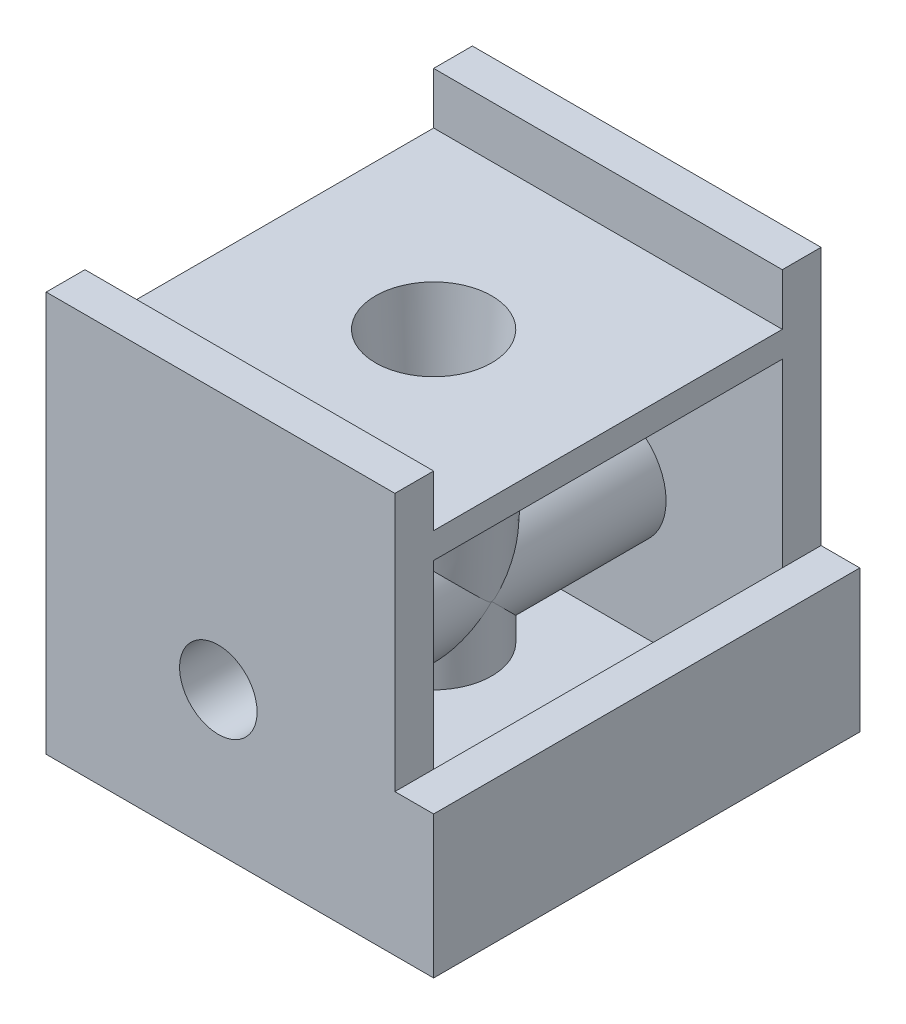
SolidWorks part; units mm, degrees
ref_plane "Front Plane" through (0, 0, 0) normal (0, 0, 1) x (1, 0, 0)
ref_plane "Top Plane" through (0, 0, 0) normal (0, 1, 0) x (1, 0, 0)
ref_plane "Right Plane" through (0, 0, 0) normal (1, 0, 0) x (0, 0, -1)
sketch "Sketch1" plane through (0, 0, 0) normal (0, 1, 0) x (1, 0, 0)
  line L0 (-16.5, 16.5) -> (16.5, 16.5)
  line L1 (-13.5, 13.5) -> (13.5, 13.5)
  line L2 (-13.5, 13.5) -> (-13.5, -13.5)
  line L3 (-13.5, -13.5) -> (13.5, -13.5)
  line L4 (13.5, 13.5) -> (13.5, -13.5)
  line L5 (-13.5, 13.5) -> (13.5, -13.5) construction
  line L6 (-13.5, -13.5) -> (13.5, 13.5) construction
  line L7 (16.5, 16.5) -> (16.5, -16.5)
  line L8 (-16.5, -16.5) -> (16.5, -16.5)
  line L9 (-16.5, 16.5) -> (-16.5, -16.5)
  point P0 (0, 0)
  dimension "D1" = 27
  dimension "D2" = 27
  dimension "D3" = 3
extrude "Boss-Extrude1" add sketch "Sketch1" along normal blind 30
sketch "Sketch3" plane through (-13.5, 0, 0) normal (1, 0, 0) x (0, 0, -1)
  line L1 (-13.5, 0) -> (13.5, 0)
  line L2 (-13.5, 0) -> (-13.5, 30)
  line L3 (-13.5, 30) -> (13.5, 30)
  line L4 (13.5, 0) -> (13.5, 30)
extrude "Cut-Extrude1" cut sketch "Sketch3" against normal blind 30
sketch "Sketch4" plane through (16.5, 0, 0) normal (1, 0, 0) x (0, 0, -1)
  line L1 (-16.5, 0) -> (16.5, 0)
  line L2 (-16.5, 0) -> (-16.5, -1)
  line L3 (-16.5, -1) -> (16.5, -1)
  line L4 (16.5, 0) -> (16.5, -1)
extrude "Boss-Extrude2" add sketch "Sketch4" against normal up to vertex (33 mm away)
sketch "Sketch5" plane through (13.5, 0, 0) normal (-1, 0, 0) x (0, 0, 1)
  line L0 (-13.5, 0) -> (-13.5, 24.4707)
  line L1 (-13.5, 30) -> (-13.5, 0) construction
  line L2 (13.5, 30) -> (13.5, 0) construction
  line L3 (-13.5, 24.4707) -> (13.5, 24.4707)
  line L4 (-13.5, 24.4707) -> (-13.5, 22.4707)
  line L5 (-13.5, 22.4707) -> (13.5, 22.4707)
  line L6 (13.5, 24.4707) -> (13.5, 22.4707)
sketch "Sketch7" plane through (0, 0, 0) normal (0, 1, 0) x (1, 0, 0)
  line L0 (13.5, 13.5) -> (9.5, 13.5)
  line L1 (13.5, 13.5) -> (-16.5, 13.5) construction
  line L2 (9.5, 13.5) -> (13.5, 9.5)
  line L3 (13.5, -13.5) -> (13.5, 13.5) construction
  line L4 (13.5, 9.5) -> (13.5, 13.5)
extrude "Boss-Extrude4" add sketch "Sketch7" along normal blind 4.8
sketch "Sketch8" plane through (0, 0, 0) normal (0, 1, 0) x (1, 0, 0)
  line L0 (13.5, 9.5) -> (9.5, 13.5)
  line L1 (9.5, 13.5) -> (13.5, 13.5)
  line L2 (13.5, 13.5) -> (13.5, 9.5)
extrude "Cut-Extrude3" cut sketch "Sketch8" along normal blind 2.8
sketch "Sketch9" plane through (0, 0, 0) normal (0, 1, 0) x (1, 0, 0)
  line L0 (13.5, -13.5) -> (13.5, -9.5)
  line L1 (13.5, -13.5) -> (13.5, 13.5) construction
  line L2 (13.5, -9.5) -> (9.5, -13.5)
  line L3 (-16.5, -13.5) -> (13.5, -13.5) construction
  line L4 (9.5, -13.5) -> (13.5, -13.5)
extrude "Boss-Extrude5" add sketch "Sketch9" along normal blind 4.8
sketch "Sketch10" plane through (0, 0, 0) normal (0, 1, 0) x (1, 0, 0)
  line L0 (9.5, -13.5) -> (13.5, -9.5)
  line L1 (13.5, -9.5) -> (13.5, -13.5)
  line L2 (13.5, -13.5) -> (9.5, -13.5)
extrude "Cut-Extrude5" cut sketch "Sketch10" along normal blind 2.8
sketch "Sketch12" plane through (0, 0, 0) normal (0, 1, 0) x (1, 0, 0)
  line L1 (13.5, 13.5) -> (-16.5, 13.5)
  line L2 (13.5, 13.5) -> (13.5, -13.5)
  line L3 (13.5, -13.5) -> (-16.5, -13.5)
  line L4 (-16.5, 13.5) -> (-16.5, -13.5)
  line L5 (-16.5, -13.5) -> (-13.5, -13.5)
  line L6 (-16.5, -13.5) -> (-16.5, 13.5)
  line L7 (-16.5, 13.5) -> (-13.5, 13.5)
  line L8 (-13.5, -13.5) -> (-13.5, 13.5)
  line M2 (-16.5, -13.5) -> (13.5, -13.5)
  line M5 (-16.5, 13.5) -> (-16.5, -13.5)
extrude "Cut-Extrude6" cut sketch "Sketch12" against normal blind 10 contours L8 L1 M2 M5
sketch "Sketch13" plane through (0, -1, 0) normal (0, -1, 0) x (1, 0, 0)
  line L1 (-16.5, 16.5) -> (-13.5, 16.5)
  line L2 (-16.5, 16.5) -> (-16.5, -20.8947)
  line L3 (-16.5, -20.8947) -> (-13.5, -20.8947)
  line L4 (-13.5, 16.5) -> (-13.5, -20.8947)
extrude "Cut-Extrude7" cut sketch "Sketch13" against normal through all
sketch "Sketch15" plane through (0, 0, 16.5) normal (0, 0, 1) x (1, 0, 0)
  line L0 (16.5, 30) -> (16.5, -1) construction
  line L1 (-13.5, -1) -> (16.5, -1)
  line L2 (-13.5, -1) -> (-13.5, 0)
  line L3 (-13.5, 0) -> (13.5, 0) construction
  line L4 (16.5, -1) -> (16.5, 0)
  line L5 (0, 0) -> (0, 10) construction
  circle A1 centre (0, 10) radius 4.5
extrude "Boss-Extrude6" add sketch "Sketch15" along direction (0, 0, 1) on the side against the normal through all
sketch "Sketch22" plane through (0, 0, 16.5) normal (0, 0, 1) x (1, 0, 0)
  line L2 (-13.5, -1) -> (-13.5, 0) construction
  line L3 (-13.5, 30) -> (-13.5, -1) construction
  line L4 (-13.5, 0) -> (13.5, 0) construction
  line L6 (-0.1714, 0) -> (-0.1714, 10) construction
  circle A0 centre (1.5, 10) radius 2.5
ref_plane "Plane1" through (0, 10, 0) normal (0, 1, 0) x (1, 0, 0)
sketch "Sketch26" plane through (13.5, 0, 0) normal (-1, 0, 0) x (0, 0, 1)
  line L0 (0, 0) -> (0, 25)
  line L1 (13.5, 0) -> (-13.5, 0) construction
  line L2 (13.5, 30) -> (13.5, 4.8) construction
  line L3 (-13.5, 26) -> (13.5, 26)
  line L4 (-13.5, 26) -> (-13.5, 24)
  line L5 (-13.5, 24) -> (13.5, 24)
  line L6 (13.5, 26) -> (13.5, 24)
  line L7 (-13.5, 26) -> (13.5, 24) construction
  line L8 (-13.5, 24) -> (13.5, 26) construction
extrude "Boss-Extrude8" add sketch "Sketch26" along direction (1, 0, 0) on the side of the normal through all
sketch "Sketch24" plane through (0, 10, 0) normal (0, 1, 0) x (1, 0, 0)
  line L0 (0, 13.5) -> (0, -13.5) construction
  line L1 (-4.5, 13.5) -> (4.5, 13.5) construction
  line L2 (4.5, -13.5) -> (-4.5, -13.5) construction
  circle A0 centre (0, 0) radius 4.5
extrude "Boss-Extrude7" add sketch "Sketch24" against normal blind 5 and the other way blind 16 draft 3 other way draft outward yes
sketch "Sketch25" plane through (0, 5, 0) normal (0, -1, 0) x (1, 0, 0)
  circle A2 centre (0, 0) radius 3
  circle A3 centre (0, 0) radius 3
  dimension "D1" = 1.5
sketch "Sketch27" plane through (0, 26, 0) normal (0, 1, 0) x (1, 0, 0)
  line L0 (-13.5, 13.5) -> (13.5, -13.5)
  line L1 (13.5, 13.5) -> (13.5, -13.5) construction
  circle A0 centre (0, 0) radius 4.5
extrude "Cut-Extrude12" cut sketch "Sketch27" against normal blind 21 draft 5 contours L0 A0 | L0 A0
sketch "Sketch28" plane through (0, 0, 0) normal (1, 0, 0) x (0, 0, -1)
  line L1 (19.0439, 32.0626) -> (-20.0344, 32.0626)
  line L2 (19.0439, 32.0626) -> (19.0439, -4.4945)
  line L3 (19.0439, -4.4945) -> (-20.0344, -4.4945)
  line L4 (-20.0344, 32.0626) -> (-20.0344, -4.4945)
sketch "Sketch30" plane through (0, 26, 0) normal (0, 1, 0) x (1, 0, 0)
  line L0 (13.5, 13.5) -> (-13.5, -13.5)
  line L1 (13.5, -13.5) -> (-13.5, 13.5)
sketch "Sketch31" plane through (0, 0, 16.5) normal (0, 0, 1) x (1, 0, 0)
  circle A0 centre (-0.1714, 10) radius 3
extrude "Cut-Extrude14" cut sketch "Sketch31" along direction (0, 0, 1) on the side against the normal blind 33
sketch "Sketch32" plane through (0, 30, 0) normal (0, 1, 0) x (1, 0, 0)
  line L0 (13.5, 13.5) -> (13.5, 17.6458)
  line L1 (13.5, 17.6458) -> (20.0045, 17.6458)
  line L2 (20.0045, 17.6458) -> (20.0045, -18.6428)
  line L3 (20.0045, -18.6428) -> (13.5, -18.6428)
  line L4 (13.5, -18.6428) -> (13.5, -13.5)
  line L5 (13.5, -13.5) -> (13.5, 13.5)
extrude "Cut-Extrude15" cut sketch "Sketch32" against normal blind 20
sketch "Sketch33" plane through (-13.5, 0, 0) normal (-1, 0, 0) x (0, 0, 1)
  line L1 (-22.3046, 36.5448) -> (29.792, 36.5448)
  line L2 (-22.3046, 36.5448) -> (-22.3046, -7.0843)
  line L3 (-22.3046, -7.0843) -> (29.792, -7.0843)
  line L4 (29.792, 36.5448) -> (29.792, -7.0843)
extrude "Cut-Extrude16" [suppressed] cut sketch "Sketch33" against normal blind 14
